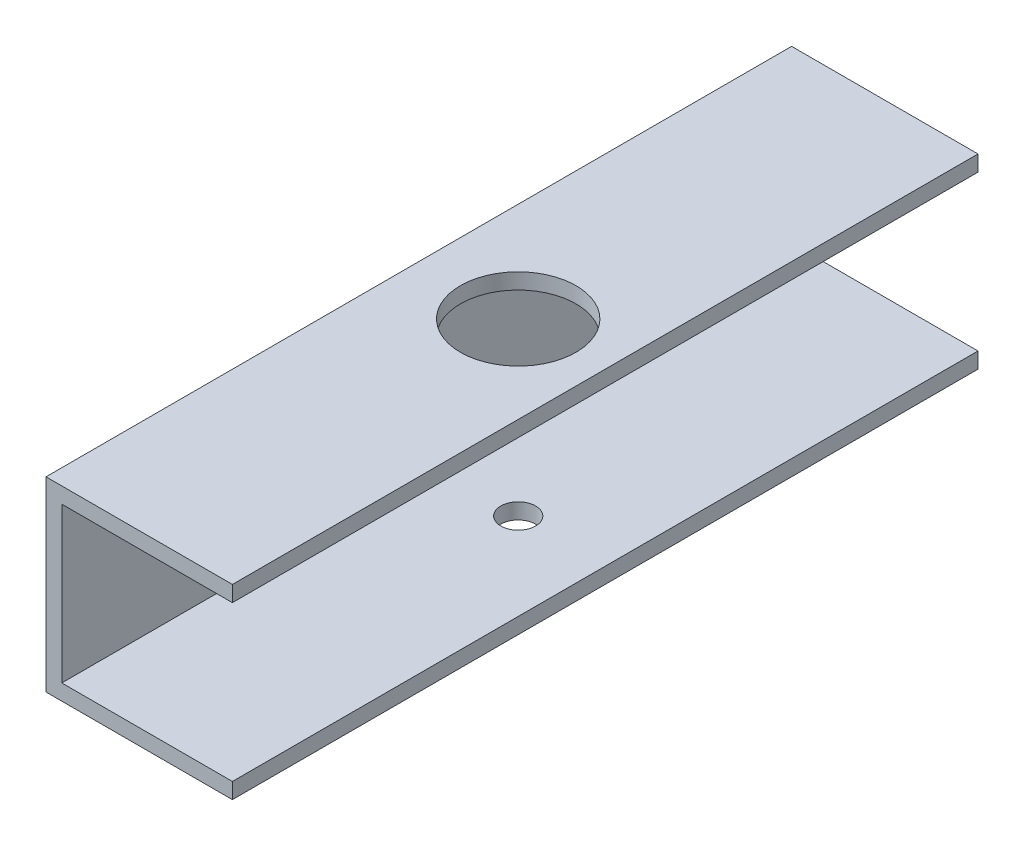
SolidWorks part; units mm, degrees
ref_plane "Front Plane" through (0, 0, 0) normal (0, 0, 1) x (1, 0, 0)
ref_plane "Top Plane" through (0, 0, 0) normal (0, 1, 0) x (1, 0, 0)
ref_plane "Right Plane" through (0, 0, 0) normal (1, 0, 0) x (0, 0, -1)
sketch "Sketch1" plane through (0, 0, 0) normal (0, 0, 1) x (1, 0, 0)
  line L0 (0, -37.5) -> (0, 37.5)
  line L1 (0, 37.5) -> (75, 37.5)
  line L2 (75, 37.5) -> (75, 31.15)
  line L3 (75, 31.15) -> (6.35, 31.15)
  line L4 (6.35, 31.15) -> (6.35, -31.15)
  line L5 (6.35, -31.15) -> (75, -31.15)
  line L6 (75, -31.15) -> (75, -37.5)
  line L7 (75, -37.5) -> (0, -37.5)
  line L8 (0, 0) -> (6.35, 0) construction
  dimension "D1" = 75
  dimension "D2" = 75
  dimension "D3" = 6.35
extrude "Boss-Extrude1" add sketch "Sketch1" along normal blind 300
sketch "Sketch2" plane through (0, 37.5, 0) normal (0, 1, 0) x (1, 0, 0)
  line L0 (40, -150) -> (0, -150) construction
  line L1 (0, -300) -> (0, 0) construction
  circle A0 centre (40, -150) radius 23.25
  dimension "D2" = 46.5
  dimension "D1" = 40
extrude "Cut-Extrude1" cut sketch "Sketch2" against normal blind 10
sketch "Sketch3" plane through (0, -37.5, 0) normal (0, -1, 0) x (1, 0, 0)
  circle A0 centre (40, 150) radius 7
  circle A1 centre (40, 150) radius 23.25 construction
  dimension "D1" = 14
extrude "Cut-Extrude2" cut sketch "Sketch3" against normal blind 10
